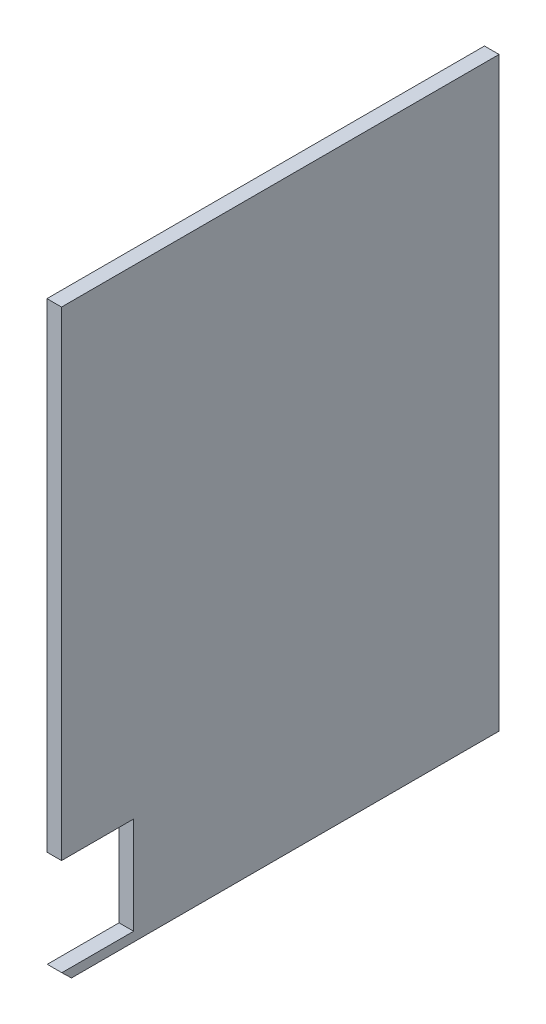
SolidWorks part; units mm, degrees
ref_plane "Front Plane" through (0, 0, 0) normal (1, 0, 0) x (0, 1, 0)
ref_plane "Top Plane" through (0, 0, 0) normal (0, 0, 1) x (0, 1, 0)
ref_plane "Right Plane" through (0, 0, 0) normal (0, 1, 0) x (-1, 0, 0)
sketch "Sketch1" plane through (0, 0, 0) normal (1, 0, 0) x (0, 1, 0)
  line L1 (-25.3548, 503.3873) -> (-178.2393, 415.1193) construction
  line L6 (-181.2393, 415.1193) -> (-25.3548, 505.1193) construction
  line L8 (211.6452, 505.1193) -> (211.6452, 325.1193)
  line L11 (-29.4444, 501.0261) -> (-25.5792, 504.9897)
  line L12 (-25.5792, 504.9897) -> (-25.5792, 475.4507)
  line L13 (151, 505.1193) -> (211.6452, 505.1193)
  line L14 (-25.5792, 475.4507) -> (14.4208, 475.4507)
  line L15 (14.4208, 475.4507) -> (14.4208, 505.1193)
  line L16 (14.4208, 505.1193) -> (151, 505.1193)
  line L22 (-29.4444, 325.1193) -> (211.6452, 325.1193)
  line L29 (-29.4444, 325.1193) -> (-29.4444, 501.0261)
  dimension "D1" = 40
  dimension "D5" = 180
extrude "Boss-Extrude1" add sketch "Sketch1" along normal blind 6
